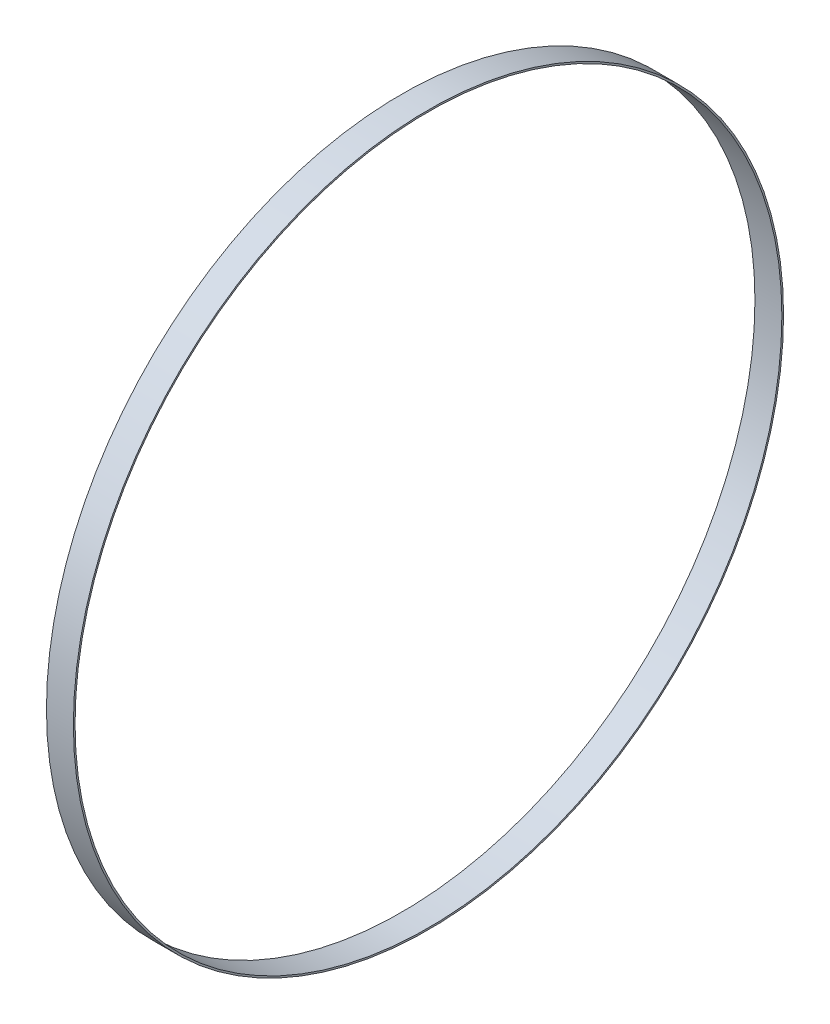
SolidWorks part; units mm, degrees
material "ASTM A36 Steel"
ref_plane "Front Plane" through (0, 0, 0) normal (0, 0, 1) x (1, 0, 0)
ref_plane "Top Plane" through (0, 0, 0) normal (0, 1, 0) x (1, 0, 0)
ref_plane "Right Plane" through (0, 0, 0) normal (1, 0, 0) x (0, 0, -1)
sketch "Sketch1" plane through (0, 0, 0) normal (1, 0, 0) x (0, 0, -1)
  circle A0 centre (0, 0) radius 1050
  circle A1 centre (0, 0) radius 1055
  dimension "D1" = 2100
  dimension "D2" = 5
extrude "Boss-Extrude1" add sketch "Sketch1" along normal blind 80
